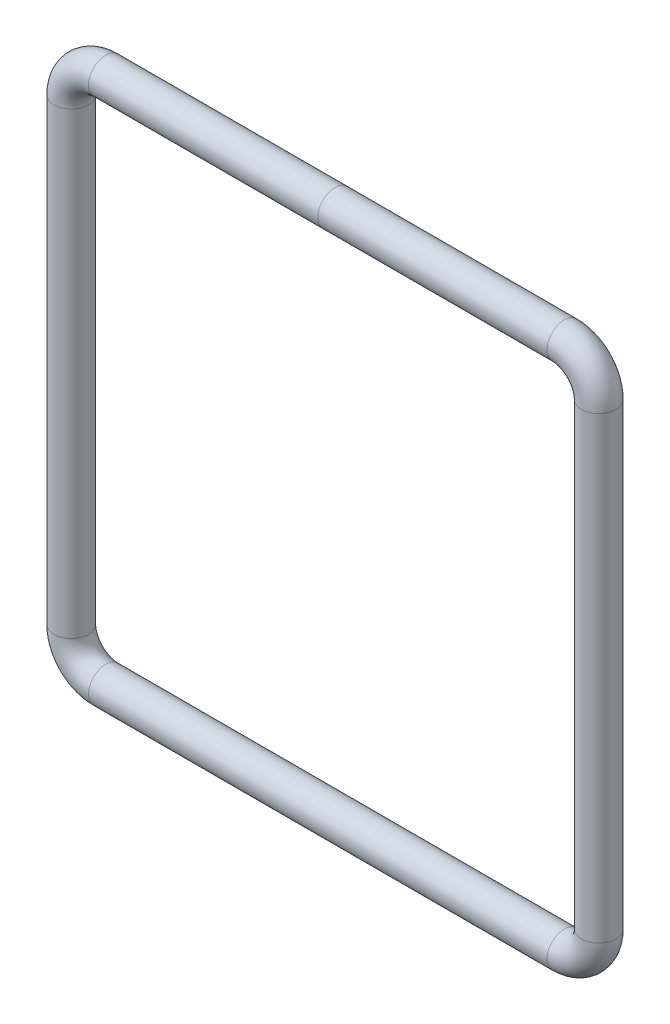
SolidWorks part; units mm, degrees
ref_plane "Plano frontal" through (0, 0, 0) normal (0, 0, 1) x (1, 0, 0)
ref_plane "Plano superior" through (0, 0, 0) normal (0, 1, 0) x (1, 0, 0)
ref_plane "Plano direito" through (0, 0, 0) normal (1, 0, 0) x (0, 0, -1)
sketch "Esboço1" plane through (0, 0, 0) normal (0, 0, 1) x (1, 0, 0)
  line L4 (27.9, 32.1) -> (-27.9, 32.1)
  line L5 (32.1, -27.9) -> (32.1, 27.9)
  line L6 (-27.9, -32.1) -> (27.9, -32.1)
  line L7 (-32.1, 27.9) -> (-32.1, -27.9)
  line L8 (27.9, 32.1) -> (-27.9, 32.1)
  line L9 (32.1, -27.9) -> (32.1, 27.9)
  line L10 (-27.9, -32.1) -> (27.9, -32.1)
  line L11 (-32.1, 27.9) -> (-32.1, -27.9)
  arc A4 (32.1, 27.9) -> (27.9, 32.1) centre (27.9, 27.9) ccw
  arc A5 (27.9, -32.1) -> (32.1, -27.9) centre (27.9, -27.9) ccw
  arc A6 (-32.1, -27.9) -> (-27.9, -32.1) centre (-27.9, -27.9) ccw
  arc A7 (-27.9, 32.1) -> (-32.1, 27.9) centre (-27.9, 27.9) ccw
  arc A8 (32.1, 27.9) -> (27.9, 32.1) centre (27.9, 27.9) ccw
  arc A9 (27.9, -32.1) -> (32.1, -27.9) centre (27.9, -27.9) ccw
  arc A10 (-32.1, -27.9) -> (-27.9, -32.1) centre (-27.9, -27.9) ccw
  arc A11 (-27.9, 32.1) -> (-32.1, 27.9) centre (-27.9, 27.9) ccw
  dimension "D1" = 0
sketch "Esboço2" plane through (0, 0, 0) normal (1, 0, 0) x (0, 0, -1)
  circle A0 centre (0, 32.1) radius 2.1
  point P0 (0, 32.1)
  dimension "D1" = 4.2
sweep "Varredura1" add profiles "Esboço2" path "Esboço1"
